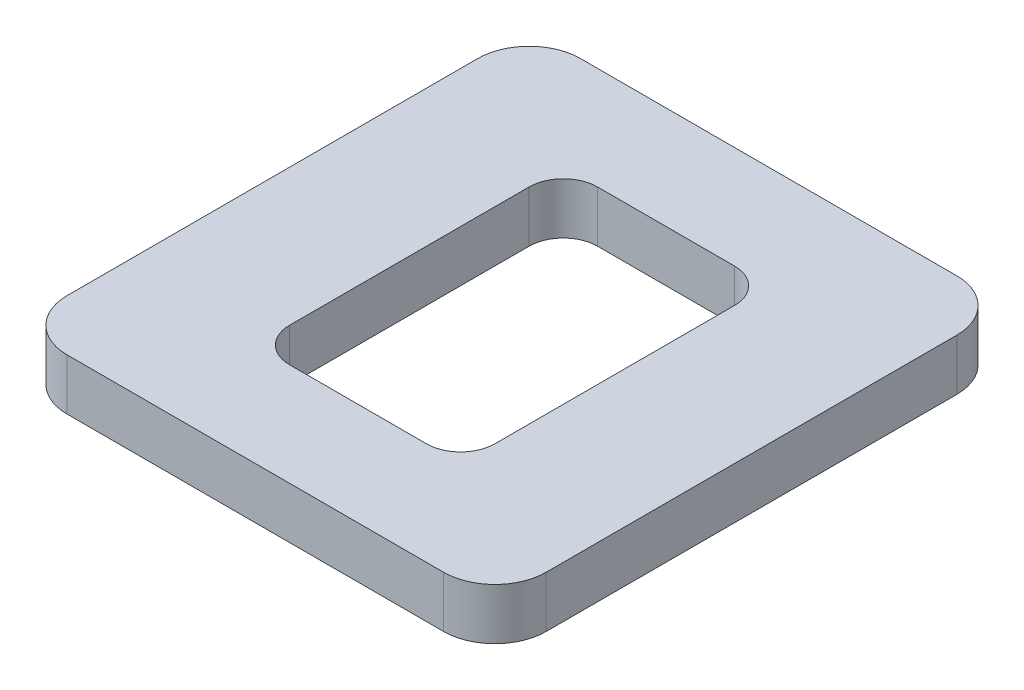
SolidWorks part; units mm, degrees
material "深灰橡胶_暂定1150kg_m3"
ref_plane "前视基准面" through (0, 0, 0) normal (0, 0, 1) x (1, 0, 0)
ref_plane "上视基准面" through (0, 0, 0) normal (0, 1, 0) x (1, 0, 0)
ref_plane "右视基准面" through (0, 0, 0) normal (1, 0, 0) x (0, 0, -1)
other "Configuration Table"
sketch "草图1" plane through (0, 0, 0) normal (0, 1, 0) x (1, 0, 0)
  line L0 (-11, -43) -> (11, -43)
  line L1 (14, -40) -> (14, -16)
  line L2 (11, -13) -> (-11, -13)
  line L3 (-14, -16) -> (-14, -40)
  line L4 (-4, -37) -> (4, -37)
  line L5 (6, -35) -> (6, -21)
  line L6 (4, -19) -> (-4, -19)
  line L7 (-6, -21) -> (-6, -35)
  arc A0 (11, -43) -> (14, -40) centre (11, -40) ccw
  arc A1 (14, -16) -> (11, -13) centre (11, -16) ccw
  arc A2 (-11, -13) -> (-14, -16) centre (-11, -16) ccw
  arc A3 (-14, -40) -> (-11, -43) centre (-11, -40) ccw
  arc A4 (4, -37) -> (6, -35) centre (4, -35) ccw
  arc A5 (6, -21) -> (4, -19) centre (4, -21) ccw
  arc A6 (-4, -19) -> (-6, -21) centre (-4, -21) ccw
  arc A7 (-6, -35) -> (-4, -37) centre (-4, -35) ccw
extrude "三毫米后门柔性压垫" add sketch "草图1" along normal blind 3 from offset 87
